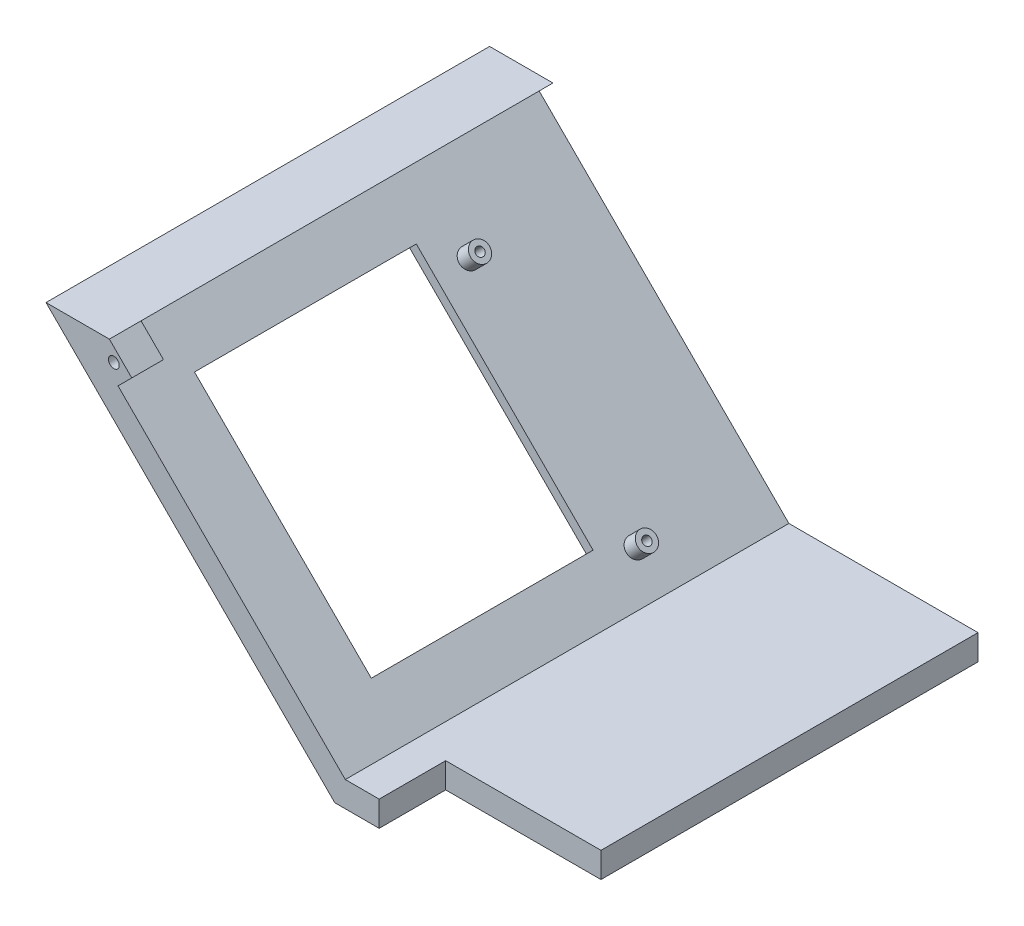
SolidWorks part; units mm, degrees
ref_plane "Plan de face" through (0, 0, 0) normal (0, 0, 1) x (1, 0, 0)
ref_plane "Plan de dessus" through (0, 0, 0) normal (0, 1, 0) x (1, 0, 0)
ref_plane "Plan de droite" through (0, 0, 0) normal (1, 0, 0) x (0, 0, -1)
sketch "Main-Sketch" plane through (0, 0, 0) normal (0, 0, 1) x (1, 0, 0)
  line L0 (0, 0) -> (0, 8)
  line L1 (0, 8) -> (-59.6863, 8)
  line L2 (-59.6863, 8) -> (-138.4931, 86.8069)
  line L3 (-154.15, 91.15) -> (-134.15, 91.15)
  line L4 (-154.15, 91.15) -> (-63, 0)
  line L5 (-63, 0) -> (0, 0)
  line L8 (-134.15, 91.15) -> (-138.4931, 86.8069)
  dimension "D1" = 8
  dimension "D2" = 8
  dimension "D3" = 63
  dimension "D4" = 135
  dimension "D5" = 20
  dimension "D6" = 154.15
extrude "Main-Extrusion" add sketch "Main-Sketch" along normal blind 140
sketch "Lcd-Sketch" plane through (0, 0, 0) normal (0, -1, 0) x (1, 0, 0)
  line L1 (0, 140) -> (-49, 140)
  line L2 (0, 140) -> (0, 119)
  line L3 (0, 119) -> (-49, 119)
  line L4 (-49, 140) -> (-49, 119)
  dimension "D1" = 21
  dimension "D2" = 49
extrude "Lcd-Hole" cut sketch "Lcd-Sketch" against normal through all
sketch "Upp-Fix-Sketch" plane through (0, 0, 140) normal (0, 0, 1) x (1, 0, 0)
  line L0 (-134.15, 91.15) -> (-138.4931, 86.8069)
  line L1 (-138.4931, 86.8069) -> (-131.4221, 79.7358)
  line L2 (-59.6863, 8) -> (-138.4931, 86.8069) construction
  line L3 (-131.4221, 79.7358) -> (-127.0789, 84.0789)
  line L4 (-127.0789, 84.0789) -> (-134.15, 91.15)
  dimension "D1" = 10
extrude "Up-Fix-Extrusion" add sketch "Upp-Fix-Sketch" against normal blind 10
hole_wizard "Fraisage pour vis à tête fraisée M31" positions "Esquisse7" profile "Esquisse6" countersink size "M3" standard "Ansi Metric" end condition up to next
sketch "Esquisse7" plane through (0, 0, 130) normal (0, 0, -1) x (-1, 0, 0)
  line L0 (127.0789, 84.0789) -> (134.15, 91.15) construction
  line L1 (131.4221, 79.7358) -> (127.0789, 84.0789) construction
  point P0 (132.7358, 85.4931)
  dimension "D1" = 3
  dimension "D2" = 5
sketch "Esquisse6" plane through (-132.7358, 85.4931, 130) normal (1, 0, 0) x (0, 1, 0)
  line L0 (0, 0) -> (0, 10)
  line L1 (0, 10) -> (1.7, 10)
  line L2 (1.7, 10) -> (1.7, 1.3)
  line L3 (1.7, 1.3) -> (3, 0)
  line L5 (3, 0) -> (0, 0)
  line L6 (-1.7, 1.3) -> (-3, 0) construction
  line L11 (0, -6.35) -> (0, 107.95) construction
  dimension "Diamètre du perçage jusqu'au prochain" = 3.4
  dimension "Profondeur du perçage jusqu'au prochain" = 10
  dimension "Diamètre du fraisage entrant" = 6
  dimension "Angle du fraisage entrant" = 90
sketch "MotorBoard-Hole-Sketch" plane through (-31.5, -31.5, 0) normal (-0.7071, -0.7071, 0) x (0, 0, 1)
  line L0 (0, 173.4533) -> (0, 44.5477) construction
  line L1 (120, 143.4533) -> (50, 143.4533)
  line L2 (120, 143.4533) -> (120, 64.5477)
  line L3 (120, 64.5477) -> (50, 64.5477)
  line L4 (50, 143.4533) -> (50, 64.5477)
  line L5 (140, 173.4533) -> (140, 44.5477) construction
  line L6 (140, 173.4533) -> (0, 173.4533) construction
  line L7 (140, 44.5477) -> (0, 44.5477) construction
  dimension "D1" = 50
  dimension "D2" = 20
  dimension "D3" = 30
  dimension "D4" = 20
extrude "MotorBoard-Hole" cut sketch "MotorBoard-Hole-Sketch" against normal through all
sketch "MotorBoard-Window-Sketch" plane through (-31.5, -31.5, 0) normal (-0.7071, -0.7071, 0) x (0, 0, 1)
  line L0 (120, 64.5477) -> (120, 143.4533) construction
  line L1 (128, 151.4533) -> (42, 151.4533)
  line L2 (128, 151.4533) -> (128, 56.5477)
  line L3 (128, 56.5477) -> (42, 56.5477)
  line L4 (42, 151.4533) -> (42, 56.5477)
  line L5 (120, 143.4533) -> (50, 143.4533) construction
  line L6 (50, 143.4533) -> (50, 64.5477) construction
  line L7 (50, 64.5477) -> (120, 64.5477) construction
  dimension "D1" = 8
  dimension "D2" = 8
  dimension "D3" = 8
  dimension "D4" = 8
extrude "MotorBoard-Window" cut sketch "MotorBoard-Window-Sketch" against normal blind 5
sketch "MotorBoard-Fix-Sketch" plane through (-25.8431, -25.8431, 0) normal (0.7071, 0.7071, 0) x (0, 0, -1)
  line L0 (-140, 47.8614) -> (-140, 149.3112) construction
  line L1 (-140, 47.8614) -> (0, 47.8614) construction
  circle A0 centre (-39.5, 60.3614) radius 3
  circle A1 centre (-39.5, 134.8614) radius 3
  dimension "D1" = 6
  dimension "D2" = 74.5
  dimension "D3" = 100.5
  dimension "D4" = 12.5
extrude "MotorBoard-Fix-Extrusion" add sketch "MotorBoard-Fix-Sketch" along normal blind 5
sketch "MotorBoard-Fix-Hole-Sketch" plane through (-22.3076, -22.3076, 0) normal (0.7071, 0.7071, 0) x (0, 0, -1)
  circle A0 centre (-39.5, 60.3614) radius 1.35
  circle A1 centre (-39.5, 134.8614) radius 1.35
  circle A2 centre (-39.5, 134.8614) radius 3 construction
  dimension "D1" = 2.7
extrude "MotorBoard-Fix-Hole" cut sketch "MotorBoard-Fix-Hole-Sketch" against normal through all
